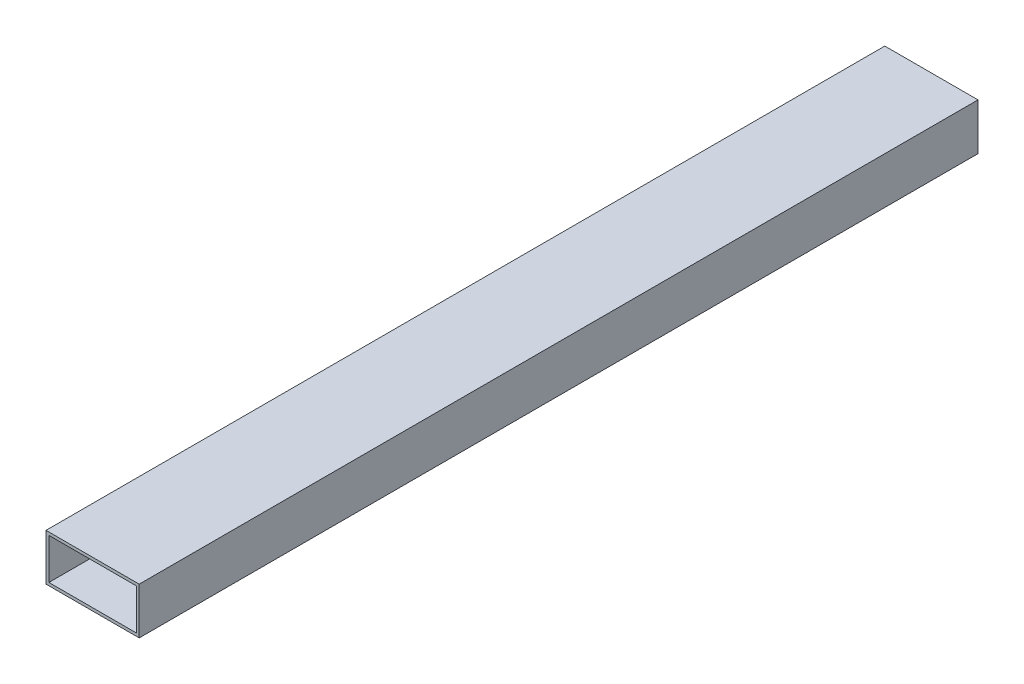
SolidWorks part; units mm, degrees
ref_plane "Front Plane" through (0, 0, 0) normal (0, 0, 1) x (1, 0, 0)
ref_plane "Top Plane" through (0, 0, 0) normal (0, 1, 0) x (1, 0, 0)
ref_plane "Right Plane" through (0, 0, 0) normal (1, 0, 0) x (0, 0, -1)
sketch "Sketch1" plane through (0, 0, 0) normal (0, 0, 1) x (1, 0, 0)
  line L0 (1.5875, 23.8125) -> (49.2125, 23.8125)
  line L1 (0, 0) -> (50.8, 0)
  line L2 (0, 0) -> (0, 25.4)
  line L3 (0, 25.4) -> (50.8, 25.4)
  line L4 (50.8, 0) -> (50.8, 25.4)
  line L5 (49.2125, 1.5875) -> (49.2125, 23.8125)
  line L6 (1.5875, 1.5875) -> (49.2125, 1.5875)
  line L7 (1.5875, 1.5875) -> (1.5875, 23.8125)
  dimension "D1" = 25.4
  dimension "D2" = 50.8
  dimension "D3" = 1.5875
extrude "Boss-Extrude1" add sketch "Sketch1" along normal blind 457.2
sketch "Sketch2" plane through (0, 25.4, 0) normal (0, 1, 0) x (1, 0, 0)
  line L0 (0, -457.2) -> (0, 0)
  line L1 (0, -228.6) -> (50.8, -228.6)
  line L2 (50.8, -457.2) -> (50.8, 0) construction
